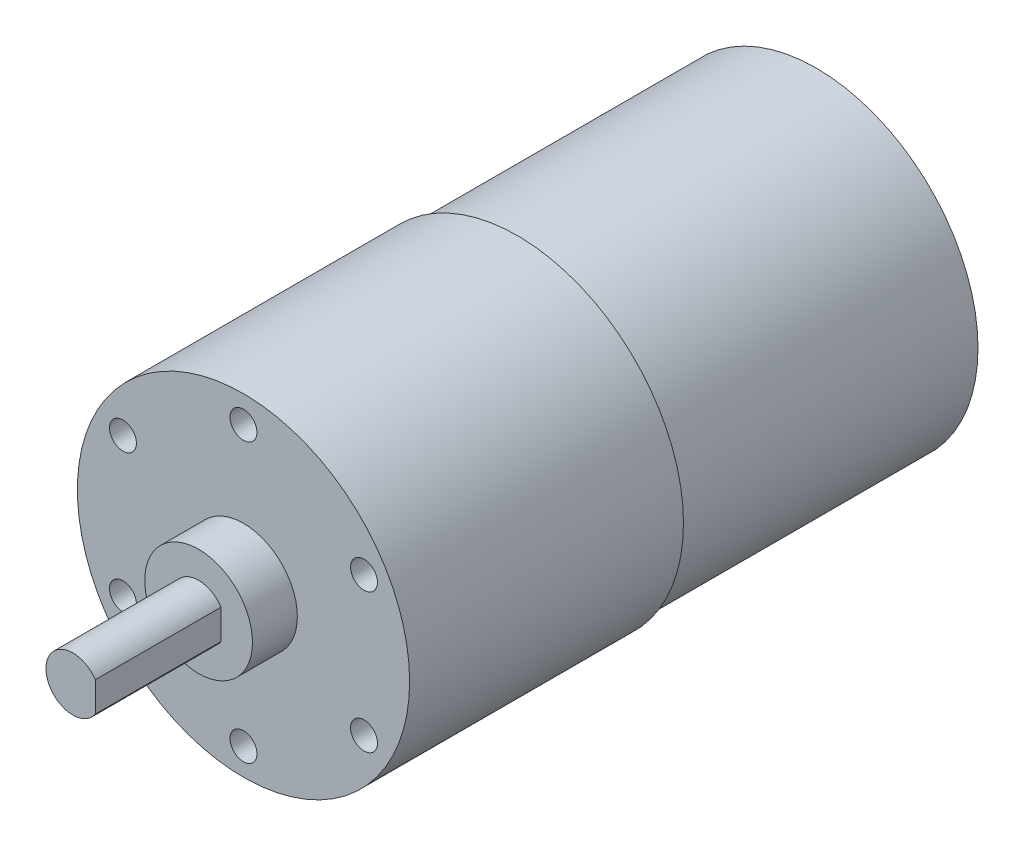
SolidWorks part; units mm, degrees
material "1060 合金"
ref_plane "前视基准面" through (0, 0, 0) normal (0, 0, 1) x (1, 0, 0)
ref_plane "上视基准面" through (0, 0, 0) normal (0, 1, 0) x (1, 0, 0)
ref_plane "右视基准面" through (0, 0, 0) normal (1, 0, 0) x (0, 0, -1)
sketch "草图1" plane through (0, 0, 0) normal (1, 0, 0) x (0, 0, -1)
  line L0 (0, 0) -> (54.6575, 0) construction
  line L1 (0, 0) -> (0, 3)
  line L2 (0, 3) -> (14, 3)
  line L3 (14, 3) -> (14, 6)
  line L4 (14, 6) -> (19, 6)
  line L5 (19, 6) -> (19, 18.5)
  line L6 (19, 18.5) -> (49.5, 18.5)
  line L7 (49.5, 18.5) -> (49.5, 18)
  line L8 (49.5, 18) -> (82.8, 18)
  line L9 (82.8, 18) -> (82.8, 0)
  line L10 (82.8, 0) -> (0, 0)
  dimension "D1" = 3
  dimension "D2" = 6
  dimension "D3" = 18.5
  dimension "D4" = 18
  dimension "D5" = 14
  dimension "D6" = 5
  dimension "D7" = 30.5
  dimension "D8" = 33.3
revolve "旋转1" add sketch "草图1" angle 360 about L0
sketch "草图2" plane through (0, 0, -19) normal (0, 0, 1) x (1, 0, 0)
  circle A0 centre (0, 0) radius 15.5 construction
  circle A1 centre (0, 15.5) radius 1.5
  circle A2 centre (13.4234, 7.75) radius 1.5
  circle A3 centre (13.4234, -7.75) radius 1.5
  circle A4 centre (0, -15.5) radius 1.5
  circle A5 centre (-13.4234, -7.75) radius 1.5
  circle A6 centre (-13.4234, 7.75) radius 1.5
  dimension "D1" = 31
  dimension "D2" = 3
  dimension "D3" = 6
extrude "切除-拉伸1" cut sketch "草图2" against normal blind 10
sketch "草图3" plane through (0, 0, 0) normal (0, 1, 0) x (1, 0, 0)
  line L0 (3, 0) -> (3, 14) construction
  line L1 (3.5, 14) -> (2.5, 14)
  line L2 (3.5, 14) -> (3.5, 0)
  line L3 (3.5, 0) -> (2.5, 0)
  line L4 (2.5, 14) -> (2.5, 0)
  line L5 (3.5, 14) -> (2.5, 0) construction
  line L6 (3.5, 0) -> (2.5, 14) construction
  point P0 (3, 7)
  dimension "D1" = 1
  dimension "D2" = 14
extrude "切除-拉伸2" cut sketch "草图3" against normal through all and the other way through all
